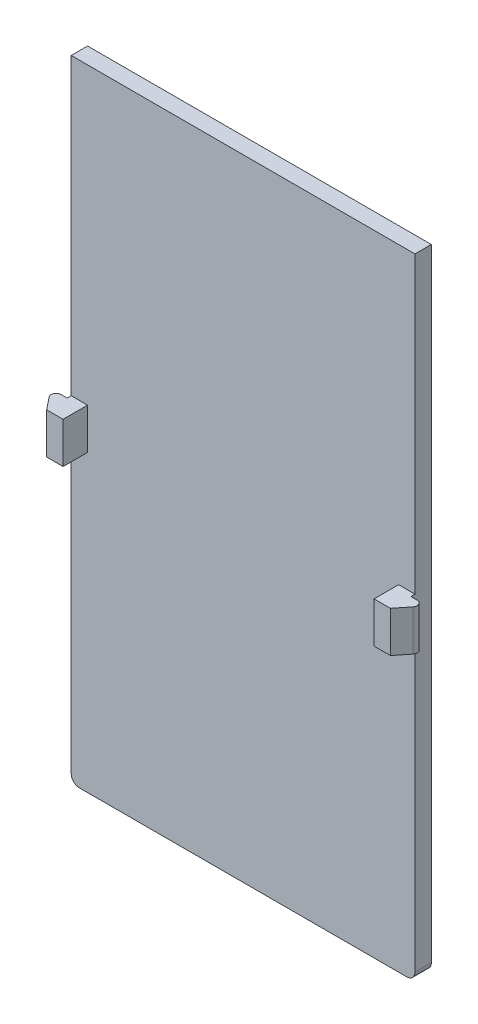
SolidWorks part; units mm, degrees
ref_plane "Front Plane" through (0, 0, 0) normal (0, 0, 1) x (1, 0, 0)
ref_plane "Top Plane" through (0, 0, 0) normal (0, 1, 0) x (1, 0, 0)
ref_plane "Right Plane" through (0, 0, 0) normal (1, 0, 0) x (0, 0, -1)
sketch "Sketch1" plane through (0, 0, 0) normal (0, 0, 1) x (1, 0, 0)
  line L1 (0, 0) -> (46, 0)
  line L2 (0, 0) -> (0, -79)
  line L3 (0, -79) -> (46, -79)
  line L4 (46, 0) -> (46, -79)
  dimension "D1" = 79
  dimension "D2" = 46
extrude "Boss-Extrude1" add sketch "Sketch1" along normal blind 2
sketch "Sketch2" plane through (0, 0, 2) normal (0, 0, 1) x (1, 0, 0)
  line L0 (46, 0) -> (0, 0) construction
  line L1 (2, -36) -> (4, -36)
  line L2 (2, -36) -> (2, -41)
  line L3 (2, -41) -> (4, -41)
  line L4 (4, -36) -> (4, -41)
  line L5 (42, -36) -> (44, -36)
  line L6 (42, -36) -> (42, -41)
  line L7 (42, -41) -> (44, -41)
  line L8 (44, -36) -> (44, -41)
  line L12 (0, 0) -> (0, -79) construction
  line L13 (46, -79) -> (46, 0) construction
  dimension "D1" = 36
  dimension "D2" = 5
  dimension "D3" = 5
  dimension "D4" = 36
  dimension "D5" = 2
  dimension "D6" = 2
  dimension "D7" = 2
  dimension "D8" = 2
extrude "Boss-Extrude2" add sketch "Sketch2" along normal blind 3
sketch "Sketch3" plane through (0, -41, 0) normal (0, -1, 0) x (1, 0, 0)
  line L0 (4, 5) -> (4, 7)
  line L1 (4, 7) -> (2, 7)
  line L2 (2, 7) -> (0, 5)
  line L3 (0, 5) -> (2, 5)
  line L4 (42, 5) -> (46, 5)
  line L5 (46, 5) -> (44, 7)
  line L6 (44, 7) -> (42, 7)
  line L7 (42, 7) -> (42, 5)
  line L8 (44, 5) -> (44, 2) construction
  line M8 (4, 5) -> (2, 5)
  dimension "D1" = 2
  dimension "D2" = 2
  dimension "D3" = 2
  dimension "D4" = 2
  dimension "D5" = 2
  dimension "D6" = 2
extrude "Boss-Extrude3" add sketch "Sketch3" against normal up to surface (5 mm away) contours L2 L3 L0 L1 M8 | L6 L7 L4 L5 up to face at (43, -36, 3.5)
fillet "Fillet1" radius 0.6 2 edges at (46, -38.5, 5) (0, -38.5, 5)
sketch "Sketch4" plane through (0, 0, 2) normal (0, 0, 1) x (1, 0, 0)
  line L0 (0, 0) -> (0, -79) construction
  line L1 (2, -2) -> (44, -2)
  line L2 (2, -2) -> (2, -77)
  line L3 (2, -77) -> (44, -77)
  line L4 (44, -2) -> (44, -77)
  line L5 (46, 0) -> (0, 0) construction
  line L6 (46, -79) -> (46, 0) construction
  line L7 (0, -79) -> (46, -79) construction
  line L9 (0, 0) -> (46, 0)
  line L10 (0, 0) -> (0, -79)
  line L11 (0, -79) -> (46, -79)
  line L12 (46, 0) -> (46, -79)
  dimension "D1" = 2
  dimension "D2" = 2
  dimension "D3" = 2
  dimension "D4" = 2
extrude "Cut-Extrude1" cut sketch "Sketch4" against normal blind 10
sketch "Sketch5" plane through (0, 0, 2) normal (0, 0, 1) x (1, 0, 0)
  line L0 (44, -36) -> (44, -2) construction
  line L1 (2, -2) -> (44, -2)
  line L2 (2, -2) -> (2, -1)
  line L3 (2, -1) -> (44, -1)
  line L4 (44, -2) -> (44, -1)
  dimension "D1" = 1
  dimension "D2" = 0
extrude "Boss-Extrude4" add sketch "Sketch5" against normal up to surface (2 mm away) up to face at (23, -39.5, 0)
sketch "Sketch6" plane through (0, 0, 2) normal (0, 0, 1) x (1, 0, 0)
  line L0 (44, -36) -> (44, -1) construction
  line L1 (2, -1) -> (44, -1)
  line L2 (2, -1) -> (2, 0)
  line L3 (2, 0) -> (44, 0)
  line L4 (44, -1) -> (44, 0)
  dimension "D1" = 1
  dimension "D2" = 0
extrude "Boss-Extrude5" add sketch "Sketch6" against normal up to surface (2 mm away) up to face at (23, -39, 0)
fillet "Fillet2" radius 1 2 edges at (2, -77, 1) (44, -77, 1)
sketch "Sketch7" plane through (0, -41, 0) normal (0, -1, 0) x (1, 0, 0)
  line L0 (4, 7) -> (4, 2) construction
  line L1 (4, 5) -> (-1.2201, 5)
  line L2 (4, 5) -> (4, 7.4937)
  line L3 (4, 7.4937) -> (-1.2201, 7.4937)
  line L4 (-1.2201, 5) -> (-1.2201, 7.4937)
  line L5 (42, 7) -> (42, 2) construction
  line L6 (42, 5) -> (46.4471, 5)
  line L7 (42, 5) -> (42, 7.906)
  line L8 (42, 7.906) -> (46.4471, 7.906)
  line L9 (46.4471, 5) -> (46.4471, 7.906)
extrude "Cut-Extrude2" cut sketch "Sketch7" against normal blind 10
sketch "Sketch8" plane through (0, -41, 0) normal (0, -1, 0) x (1, 0, 0)
  line L0 (2, 5) -> (0, 2.5)
  line L1 (0, 2.5) -> (4, 2.5)
  line L2 (4, 5) -> (4, 2) construction
  line L3 (4, 2.5) -> (4, 5)
  line L4 (4, 5) -> (2, 5)
  line L5 (42, 2.5) -> (46, 2.5)
  line L6 (42, 5) -> (42, 2) construction
  line L7 (46, 2.5) -> (44, 5)
  line L8 (44, 5) -> (42, 5)
  line L9 (42, 5) -> (42, 2.5)
  line L10 (2, 2) -> (4, 2) construction
  line L12 (44, 5) -> (44, 2) construction
  dimension "D1" = 0.5
  dimension "D2" = 2
extrude "Boss-Extrude6" add sketch "Sketch8" against normal up to surface (5 mm away) up to face at (3, -36, 3.5)
fillet "Fillet3" radius 0.6 2 edges at (0, -38.5, 2.5) (46, -38.5, 2.5)
